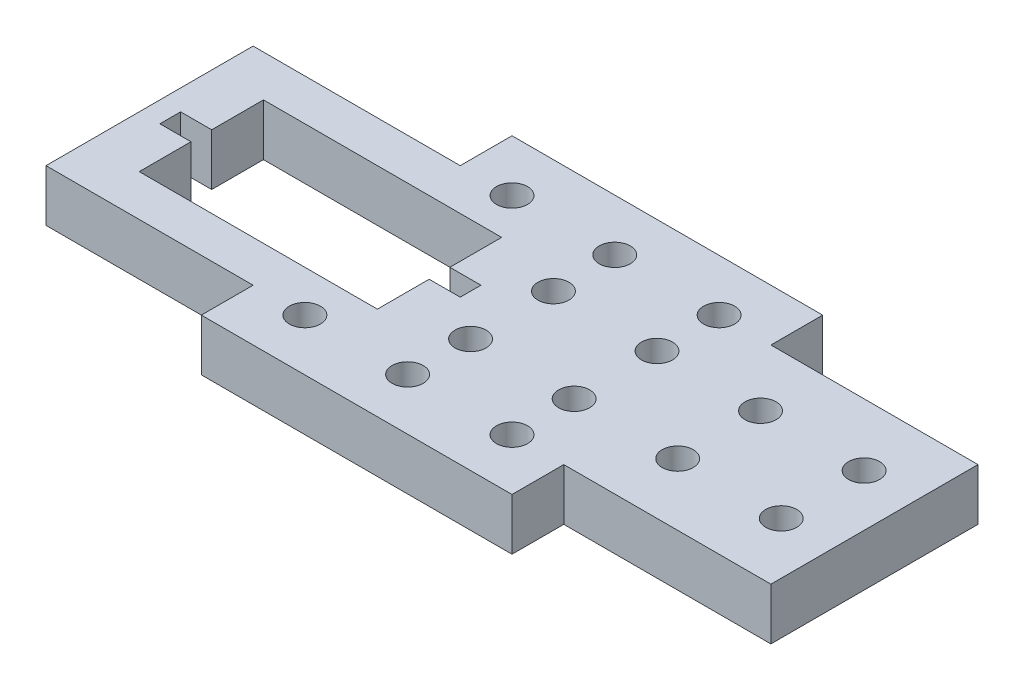
SolidWorks part; units mm, degrees
ref_plane "前视基准面" through (0, 0, 0) normal (0, 0, 1) x (1, 0, 0)
ref_plane "上视基准面" through (0, 0, 0) normal (0, 1, 0) x (1, 0, 0)
ref_plane "右视基准面" through (0, 0, 0) normal (1, 0, 0) x (0, 0, -1)
sketch "草图1" plane through (0, 0, 0) normal (0, 1, 0) x (1, 0, 0)
  line L0 (50, 20) -> (70, 20)
  line L1 (0, 0) -> (20, 0)
  line L2 (0, 0) -> (0, 20)
  line L3 (0, 20) -> (20, 20)
  line L4 (70, 0) -> (70, 20)
  line L5 (21.482, 20) -> (48.3595, 20) construction
  line L6 (20, 20) -> (20, 25)
  line L7 (20, 25) -> (50, 25)
  line L8 (50, 20) -> (50, 25)
  line L9 (48.3595, 0) -> (21.482, 0) construction
  line L10 (20, 0) -> (20, -5)
  line L11 (20, -5) -> (50, -5)
  line L12 (50, 0) -> (50, -5)
  line L13 (50, 0) -> (70, 0)
  line L14 (5, 16) -> (28, 16)
  line L15 (5, 16) -> (5, 11)
  line L16 (5, 4) -> (28, 4)
  line L17 (28, 16) -> (28, 11)
  line L18 (35, 28.9355) -> (35, -12.6103) construction
  line L19 (45, 28.9355) -> (45, -11.932) construction
  line L20 (55, 28.9355) -> (55, -10.321) construction
  line L21 (25, 46.9104) -> (25, -12.6103) construction
  line L22 (65, 29.529) -> (65, -9.3884) construction
  line L23 (76.2546, 14) -> (-14.2135, 14) construction
  line L24 (-12.6873, 6) -> (76.8481, 6) construction
  line L25 (5, 9) -> (5, 4)
  line L26 (28, 11) -> (31, 11)
  line L28 (28, 9) -> (31, 9)
  line L29 (31, 11) -> (31, 9)
  line L30 (5, 11) -> (2, 11)
  line L31 (28, 9) -> (28, 4)
  line L32 (5, 9) -> (2, 9)
  line L33 (2, 11) -> (2, 9)
  circle A0 centre (25, 20) radius 1.5
  circle A1 centre (34.9208, 20) radius 1.5
  circle A2 centre (45, 20) radius 1.5
  circle A3 centre (35, 14) radius 1.5
  circle A4 centre (45, 14) radius 1.5
  circle A5 centre (35, 6) radius 1.5
  circle A6 centre (34.9208, 0) radius 1.5
  circle A7 centre (45, 0) radius 1.5
  circle A8 centre (45, 6) radius 1.5
  circle A9 centre (55, 14) radius 1.5
  circle A10 centre (55, 6) radius 1.5
  circle A11 centre (65, 14) radius 1.5
  circle A12 centre (65, 6) radius 1.5
  circle A13 centre (25, 0) radius 1.5
  point P30 (20, 22.5)
  point P72 (3.5, 11)
  dimension "D20" = 5
  dimension "D1" = 70
  dimension "D2" = 20
  dimension "D3" = 30
  dimension "D4" = 30
  dimension "D5" = 5
  dimension "D6" = 5
  dimension "D7" = 20
  dimension "D8" = 20
  dimension "D9" = 23
  dimension "D10" = 12
  dimension "D11" = 4
  dimension "D12" = 5
  dimension "D13" = 10
  dimension "D14" = 15
  dimension "D15" = 10
  dimension "D16" = 10
  dimension "D17" = 10
  dimension "D18" = 6
  dimension "D19" = 6
  dimension "D21" = 5
  dimension "D22" = 5
  dimension "D23" = 5
extrude "凸台-拉伸1" add sketch "草图1" along normal blind 5
